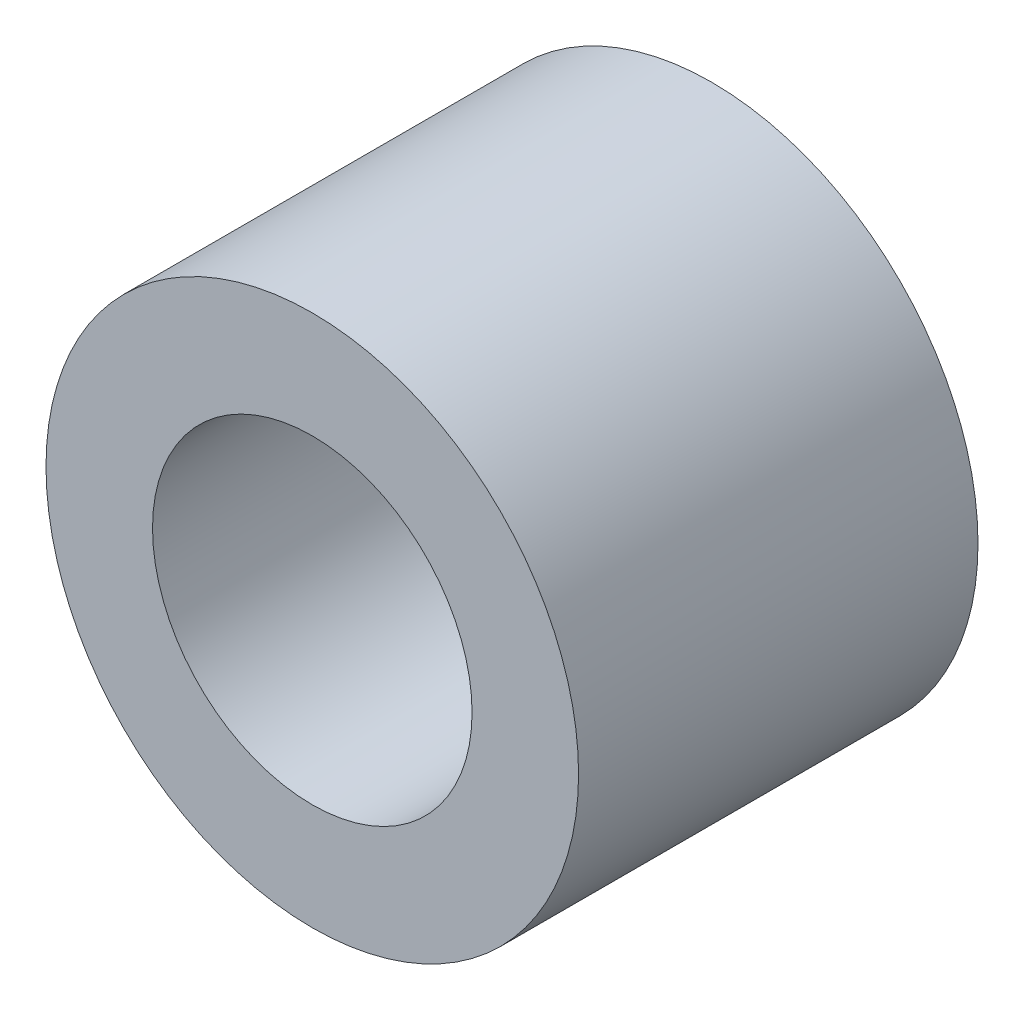
SolidWorks part; units mm, degrees
ref_plane "Front Plane" through (0, 0, 0) normal (0, 0, 1) x (1, 0, 0)
ref_plane "Top Plane" through (0, 0, 0) normal (0, 1, 0) x (1, 0, 0)
ref_plane "Right Plane" through (0, 0, 0) normal (1, 0, 0) x (0, 0, -1)
sketch "Sketch1" plane through (0, 0, 0) normal (0, 0, 1) x (1, 0, 0)
  circle A0 centre (0, 0) radius 3
  circle A1 centre (0, 0) radius 5
  dimension "D1" = 10
  dimension "D2" = 6
extrude "Boss-Extrude1" add sketch "Sketch1" along normal mid plane 7.5
sketch "Sketch2" plane through (0, 0, -3.75) normal (0, 0, -1) x (-1, 0, 0)
  circle A0 centre (0, 0) radius 3
  circle A1 centre (0, 0) radius 3 construction
extrude "Boss-Extrude2" add sketch "Sketch2" against normal blind 1.875
equation "\"shaft inner diameter\"= 15mm "
equation "\"shaft outer diameter\"= 20mm "
equation "\"column angle\" = 45deg "
equation "\"keyway_height\" = 1.39mm "
equation "\"keyway_width\" = 2.78mm "
equation "\"keyway_length\" = 30mm "
equation "\"steering column length\" = 555mm "
equation "\"steering wheel bolt width\" = 6mm "
equation "\"steering wheel bolt length\" = 40mm "
equation "\"bushing length\" = 40mm "
equation "\"bushing thickness\" = 3mm "
equation "\"u_joint clearance\" = 30mm "
equation "\"u_joint thickness\" = 7.5mm "
equation "\"horizontal shaft length\" = 90mm "
equation "\"short_bearing_outer_width\" = 10mm "
equation "\"column bushing diameter\" = \"primary shaft small diameter\" + 4 "
equation "\"column bushing distance\" = \"steering column length\"/4 "
equation "\"pinion width\" = 26.5mm "
equation "\"number of teeth\" = 18mm "
equation "\"D1@Boss-Extrude1\"=\"u_joint thickness\""
equation "\"D1@Boss-Extrude2\"=\"u_joint thickness\"*0.25"
equation "\"wheel base\" = 1561mm "
equation "\"track\" = 1354mm "
equation "\"turning radius\" = 2000mm "
equation "\"turn to lock\" = 0.75mm "
equation "\"steering arm length\" = 100mm "
equation "\"primary shaft small diameter\" = 16mm "
equation "\"primary shaft large diameter\" = 24mm "
equation "\"secondary shaft small diameter\" = 16mm "
equation "\"secondary shaft large diameter\" = 25mm "
equation "\"pin hole diameter\" = 10mm "
equation "\"rack hole to hole\" = 500mm "
equation "\"rack length\" = \"rack hole to hole\" + \"pin hole diameter\"*2 "
equation "\"max turning angle\" = atn(\"wheel base\" / (\"turning radius\" - 0.5 * \"track\")) "
equation "\"max travel\" = 2 * \"steering arm length\" * sin(0.5 * \"max turning angle\") "
equation "\"pitch diameter\" = \"max travel\"/(pi * \"turn to lock\") "
equation "\"pressure angle\" = 20deg "
equation "\"module\" = \"pitch diameter\" / \"number of teeth\" "
equation "\"tie rod length\" = 305mm "
equation "\"tie rod inner diameter\" = 6.6mm "
equation "\"tie rod outer diameter\" = 8.1mm "
